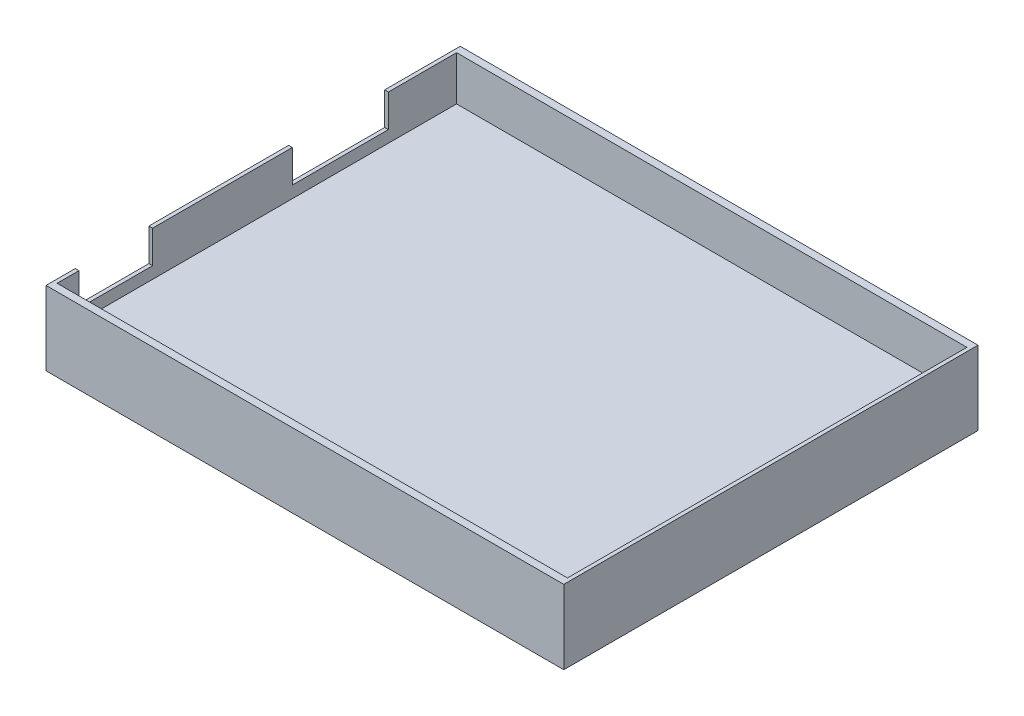
SolidWorks part; units mm, degrees
ref_plane "Front Plane" through (0, 0, 0) normal (0, 0, 1) x (1, 0, 0)
ref_plane "Top Plane" through (0, 0, 0) normal (0, 1, 0) x (1, 0, 0)
ref_plane "Right Plane" through (0, 0, 0) normal (1, 0, 0) x (0, 0, -1)
sketch "Sketch1" plane through (0, 0, 0) normal (0, 1, 0) x (1, 0, 0)
  line L1 (-35, -28) -> (35, -28)
  line L2 (-35, -28) -> (-35, 28)
  line L3 (-35, 28) -> (35, 28)
  line L4 (35, -28) -> (35, 28)
  line L5 (-35, -28) -> (35, 28) construction
  line L6 (-35, 28) -> (35, -28) construction
  point P0 (0, 0)
  dimension "D1" = 70
  dimension "D2" = 56
extrude "Boss-Extrude1" add sketch "Sketch1" along normal blind 10
sketch "Sketch2" plane through (0, 10, 0) normal (0, 1, 0) x (1, 0, 0)
  line L1 (34.5, -27) -> (-34.5, -27)
  line L2 (34.5, -27) -> (34.5, 27)
  line L3 (34.5, 27) -> (-34.5, 27)
  line L4 (-34.5, -27) -> (-34.5, 27)
  line L5 (34.5, -27) -> (-34.5, 27) construction
  line L6 (34.5, 27) -> (-34.5, -27) construction
  point P0 (0, 0)
  dimension "D1" = 69
  dimension "D2" = 54
extrude "Cut-Extrude1" cut sketch "Sketch2" against normal blind 6
sketch "Sketch3" plane through (-35, 0, 0) normal (-1, 0, 0) x (0, 0, 1)
  line L9 (-4.7962, 16.3549) -> (-17.7896, 16.3549)
  line L10 (-4.7962, 16.3549) -> (-4.7962, 5.6)
  line L11 (-4.7962, 5.6) -> (-17.7896, 5.6)
  line L12 (-17.7896, 16.3549) -> (-17.7896, 5.6)
  line L13 (24.0502, 16.1) -> (14.0964, 16.1)
  line L14 (24.0502, 16.1) -> (24.0502, 5.6)
  line L15 (24.0502, 5.6) -> (14.0964, 5.6)
  line L16 (14.0964, 16.1) -> (14.0964, 5.6)
extrude "Cut-Extrude2" cut sketch "Sketch3" against normal blind 10
